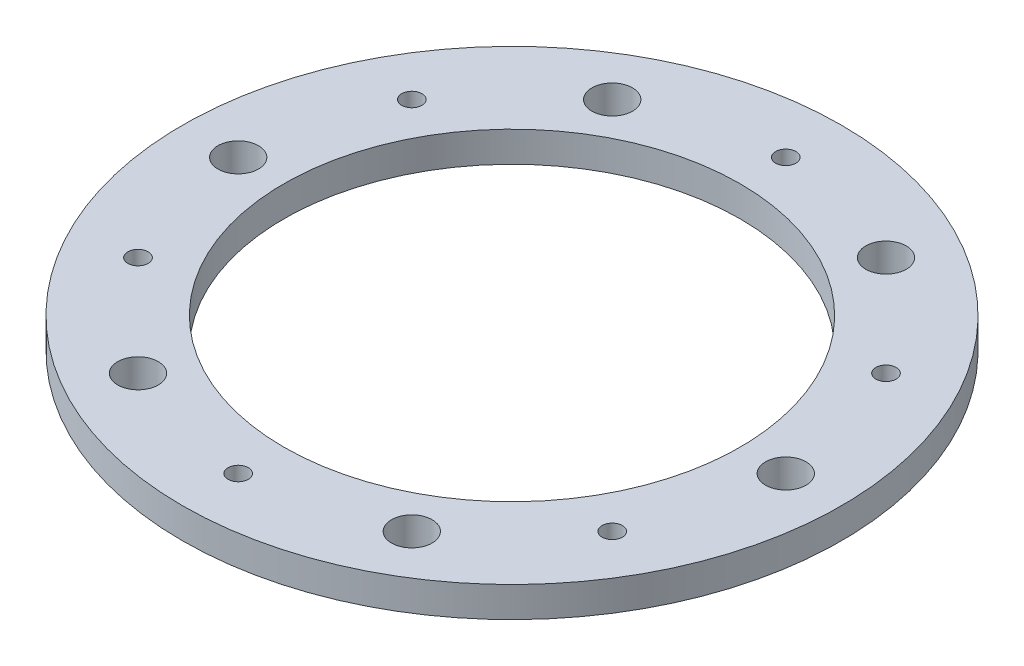
SolidWorks part; units mm, degrees
ref_plane "Front Plane" through (0, 0, 0) normal (0, 0, 1) x (1, 0, 0)
ref_plane "Top Plane" through (0, 0, 0) normal (0, 1, 0) x (1, 0, 0)
ref_plane "Right Plane" through (0, 0, 0) normal (1, 0, 0) x (0, 0, -1)
sketch "Sketch1" plane through (0, 0, 0) normal (0, 1, 0) x (1, 0, 0)
  circle A0 centre (0, 0) radius 32.5
  circle A1 centre (0, 0) radius 27 construction
  circle A2 centre (0, 27) radius 1
  circle A3 centre (23.3827, 13.5) radius 1
  circle A4 centre (23.3827, -13.5) radius 1
  circle A5 centre (0, -27) radius 1
  circle A6 centre (-23.3827, -13.5) radius 1
  circle A7 centre (-23.3827, 13.5) radius 1
  point P18 (0, 0)
  dimension "D1" = 65
  dimension "D2" = 54
  dimension "D3" = 2
  dimension "D4" = 6
extrude "Boss-Extrude1" add sketch "Sketch1" along normal blind 3
sketch "Sketch2" plane through (0, 3, 0) normal (0, 1, 0) x (1, 0, 0)
  line L0 (-13.5, 23.3827) -> (0, 0) construction
  line L1 (0, 0) -> (24.248, 0) construction
  circle A0 centre (0, 0) radius 22.5
  circle A1 centre (0, 0) radius 27 construction
  circle A2 centre (-13.5, 23.3827) radius 2
  circle A3 centre (13.5, 23.3827) radius 2
  circle A4 centre (27, 0) radius 2
  circle A5 centre (13.5, -23.3827) radius 2
  circle A6 centre (-13.5, -23.3827) radius 2
  circle A7 centre (-27, 0) radius 2
  point P19 (0, 0)
  dimension "D1" = 45
  dimension "D2" = 54
  dimension "D3" = 4
  dimension "D4" = 120
  dimension "D5" = 6
extrude "Cut-Extrude1" cut sketch "Sketch2" against normal through all
